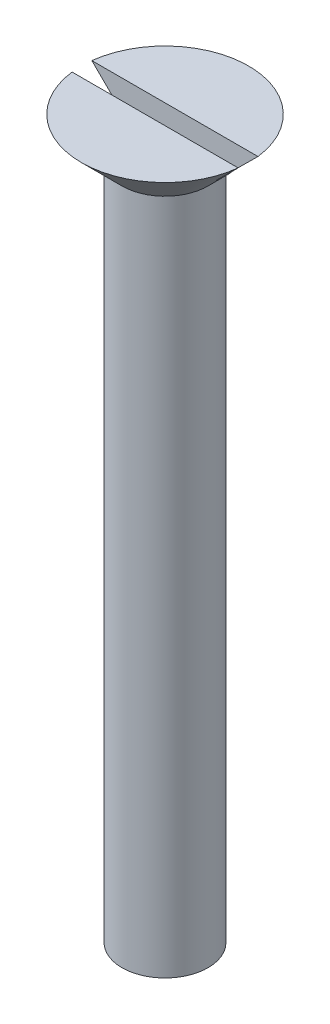
SolidWorks part; units mm, degrees
ref_plane "Front Plane" through (0, 0, 0) normal (0, 0, 1) x (1, 0, 0)
ref_plane "Top Plane" through (0, 0, 0) normal (0, 1, 0) x (1, 0, 0)
ref_plane "Right Plane" through (0, 0, 0) normal (1, 0, 0) x (0, 0, -1)
sketch "Sketch1" plane through (0, 0, 0) normal (0, 0, 1) x (1, 0, 0)
  line L0 (0, 17.3272) -> (0, -18.3435) construction
  line L1 (0, -17.2342) -> (-1.5, -17.2342)
  line L2 (-1.5, -17.2342) -> (-1.5, 6.3516)
  line L3 (-1.5, 6.3516) -> (-2.9142, 7.7658)
  line L4 (-2.9142, 7.7658) -> (0, 7.7658)
  line L5 (0, -17.2342) -> (0, 7.7658)
  dimension "D1" = 25
  dimension "D2" = 45
  dimension "D3" = 3
  dimension "D4" = 2
revolve "Revolve1" add sketch "Sketch1" angle 360 about L0
sketch "Sketch2" plane through (0, 0, 0) normal (1, 0, 0) x (0, 0, -1)
  line L0 (2.9142, 7.7658) -> (-2.9142, 7.7658) construction
  line L1 (0.3446, 8.566) -> (-0.3446, 8.566)
  line L2 (0.3446, 8.566) -> (0.3446, 6.9657)
  line L3 (0.3446, 6.9657) -> (-0.3446, 6.9657)
  line L4 (-0.3446, 8.566) -> (-0.3446, 6.9657)
  line L5 (0.3446, 8.566) -> (-0.3446, 6.9657) construction
  line L6 (0.3446, 6.9657) -> (-0.3446, 8.566) construction
  point P0 (0, 7.7658)
extrude "Cut-Extrude1" cut sketch "Sketch2" against normal through all both and the other way through all
